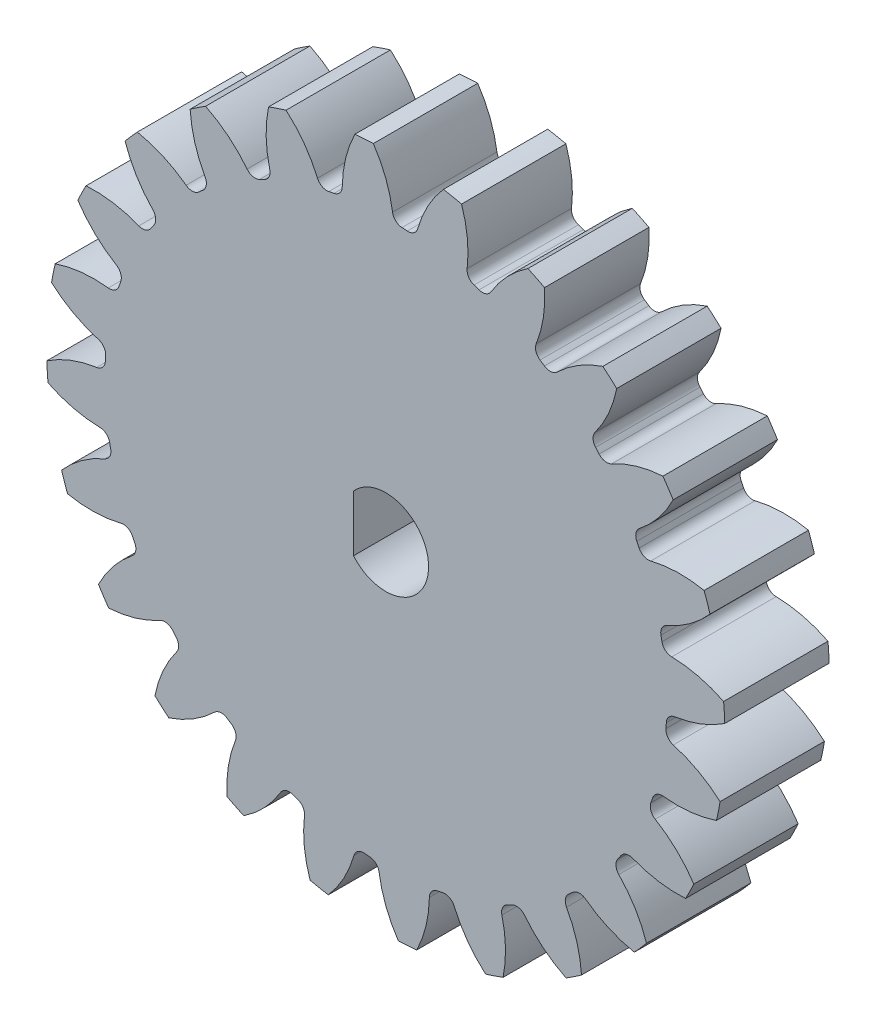
SolidWorks part; units mm, degrees
ref_plane "Front" through (0, 0, 0) normal (0, 0, 1) x (1, 0, 0)
ref_plane "Top" through (0, 0, 0) normal (0, 1, 0) x (1, 0, 0)
ref_plane "Right" through (0, 0, 0) normal (1, 0, 0) x (0, 0, -1)
sketch "Sketch3" plane through (0, 0, 0) normal (0, 0, 1) x (1, 0, 0)
  circle A0 centre (0, 0) radius 20.6375
  dimension "od" = 41.275
extrude "gearBody" add sketch "Sketch3" along normal blind 6.35
sketch "Sketch2" plane through (0, 0, 0) normal (0, 0, 1) x (1, 0, 0)
  line L0 (0, 0) -> (16.5385, 6.8505) construction
  line L1 (22.0347, -5.709) -> (0, 0) construction
  line L2 (0, 0) -> (36.3143, 0) construction
  line L3 (19.05, -0.043) -> (18.8852, -2.5004) construction
  line L5 (18.9676, -1.2717) -> (0, 0) construction
  line L7 (0, 0) -> (17.9011, 0) construction
  arc A0 (17.8975, -0.3593) -> (17.7853, -2.0332) centre (0, 0) ccw construction
  arc A1 (20.6236, 0.7563) -> (20.3381, -3.5027) centre (0, 0) ccw construction
  arc A2 (19.05, -0.043) -> (18.8852, -2.5004) centre (0, 0) ccw construction
  arc A3 (17.0444, -1.304) -> (17.0659, -0.983) centre (0, 0) ccw
  arc A4 (22.0347, -5.709) -> (17.4884, -1.9416) centre (15.476, -8.9969) ccw
  arc A5 (22.0347, -5.709) -> (22.5996, 2.7164) centre (0, 0) ccw
  arc A6 (22.5996, 2.7164) -> (17.5911, -0.4103) centre (16.5385, 6.8505) cw
  arc A7 (17.0659, -0.983) -> (17.5911, -0.4103) centre (17.6793, -1.0183) cw
  arc A8 (17.4884, -1.9416) -> (17.0444, -1.304) centre (17.657, -1.3509) cw
  point P6 (22.5996, 2.7164)
  point P22 (22.0347, -5.709)
  dimension "baseDia" = 35.8023
  dimension "od" = 41.275
  dimension "pd" = 38.1
  dimension "rd" = 34.1884
  dimension "rFillet" = 0.6144
  dimension "pointX" = 22.5996
  dimension "pointY" = 2.7164
  dimension "CTT" = 2.4574
  dimension "flankCenterAngle" = 22.5
extrude "toothCut" cut sketch "Sketch2" along normal through all
pattern_circular "CirPattern1" count 24 over 360 about axis through (0, 0, 0) along (0, 0, 1) of "toothCut"
sketch "hub1Dia" plane through (0, 0, 0) normal (0, 0, -1) x (-1, 0, 0)
  circle A0 centre (0, 0) radius 12.7
  dimension "hub1Dia" = 25.4
sketch "hub2Dia" plane through (0, 0, 6.35) normal (0, 0, 1) x (1, 0, 0)
  circle A0 centre (0, 0) radius 12.7
  dimension "hub2dia" = 25.4
sketch "boreDia" plane through (0, 0, 0) normal (0, 0, 1) x (1, 0, 0)
  circle A0 centre (0, 0) radius 6.35
  dimension "boreDia" = 12.7
sketch "Sketch4" plane through (0, 0, 0) normal (0, 0, -1) x (-1, 0, 0)
  line L0 (1.9685, -1.7039) -> (1.9685, 1.7039)
  line L1 (-2.6035, 4.8001) -> (-2.6035, -4.732) construction
  arc A0 (1.9685, 1.7039) -> (1.9685, -1.7039) centre (0, 0) ccw
  dimension "D1" = 5.207
  dimension "D2" = 4.572
extrude "Cut-Extrude1" cut sketch "Sketch4" against normal through all
sketch "Sketch5" plane through (0, 0, 0) normal (0, 1, 0) x (1, 0, 0)
  line L0 (0, 0) -> (0, 6.4123) construction
sketch "Sketch6" plane through (0, 0, 0) normal (0, 0, 1) x (1, 0, 0)
  circle A0 centre (0, 0) radius 2.6035 construction
equation "\"tightTol\"= 0.005in"
equation "\"normTol\"= 0.01in"
equation "\"looseTol\"= 0.02in"
equation "\"D1@Sketch4\"=\"tightTol\"+0.2in"
equation "\"D2@Sketch4\"=\"tightTol\"+0.175"
